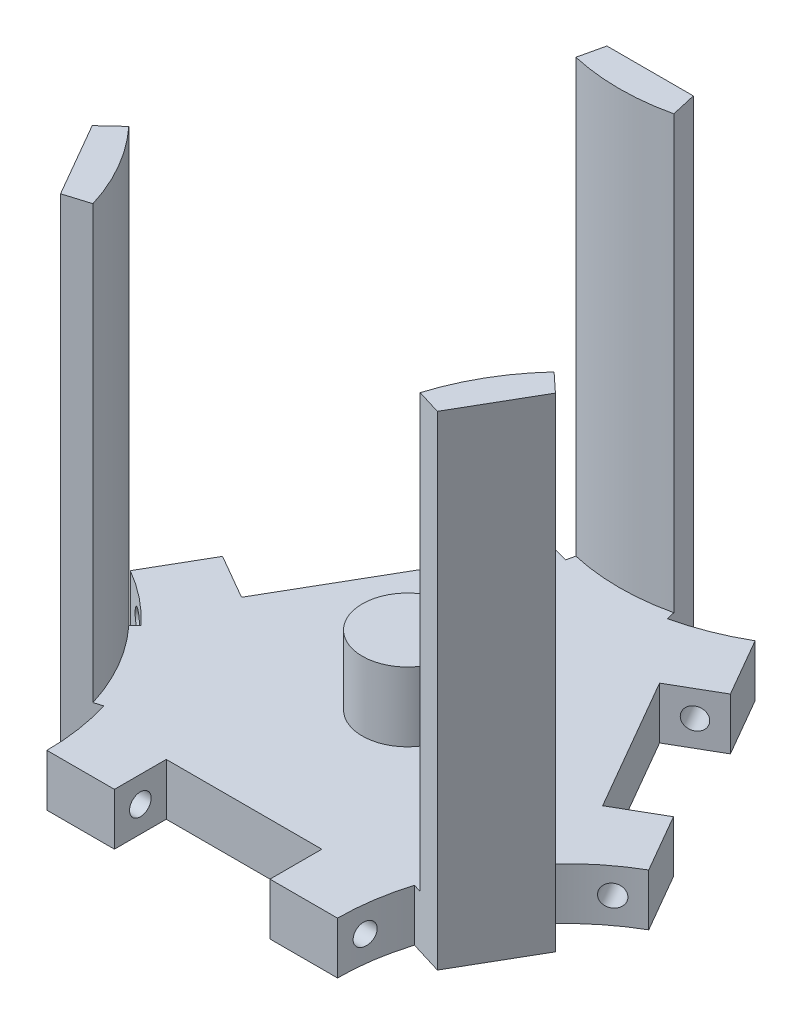
SolidWorks part; units mm, degrees
ref_plane "Front Plane" through (0, 0, 0) normal (0, 0, 1) x (1, 0, 0)
ref_plane "Top Plane" through (0, 0, 0) normal (0, 1, 0) x (1, 0, 0)
ref_plane "Right Plane" through (0, 0, 0) normal (1, 0, 0) x (0, 0, -1)
sketch "Sketch1" plane through (0, 0, 0) normal (0, 1, 0) x (1, 0, 0)
  line L0 (0, 0) -> (43.1834, 0) construction
  line L1 (43.1834, 0) -> (21.5917, 37.3979) construction
  line L2 (21.5917, 37.3979) -> (0, 0) construction
  line L3 (6.5917, 11.4171) -> (15, 25.9808)
  line L4 (28.1834, 25.9808) -> (36.5917, 11.4171)
  line L5 (13.1834, 0) -> (30, 0)
  line L6 (10.7958, 18.6989) -> (21.5917, 12.466) construction
  line L7 (21.5917, 12.466) -> (32.3875, 18.6989) construction
  line L8 (21.5917, 12.466) -> (21.5917, 0) construction
  line L9 (0, 0) -> (21.5917, 12.466) construction
  line L10 (21.5917, 12.466) -> (43.1834, 0) construction
  line L11 (21.5917, 12.466) -> (21.5917, 37.3979) construction
  line L12 (9.6546, 8.9769) -> (8.1898, 7.6152)
  line L13 (12.6016, 3.8727) -> (10.6898, 3.285)
  line L14 (8.1898, 7.6152) -> (10.6898, 3.285)
  line L15 (33.5287, 8.9769) -> (34.9935, 7.6152)
  line L16 (30.5818, 3.8727) -> (32.4935, 3.285)
  line L17 (34.9935, 7.6152) -> (32.4935, 3.285)
  line L18 (18.6448, 24.5483) -> (19.0917, 26.4977)
  line L19 (24.5386, 24.5483) -> (24.0917, 26.4977)
  line L20 (19.0917, 26.4977) -> (24.0917, 26.4977)
  arc A3 (6.5917, 11.4171) -> (9.6546, 8.9769) centre (0.0017, 0.0029) cw
  arc A4 (13.1834, 0) -> (12.6016, 3.8727) centre (0.0034, 0) ccw
  arc A5 (36.5917, 11.4171) -> (33.5287, 8.9769) centre (43.1817, 0.0029) ccw
  arc A6 (30, 0) -> (30.5818, 3.8727) centre (43.18, 0) cw
  arc A7 (15, 25.9808) -> (18.6448, 24.5483) centre (21.59, 37.395) ccw
  arc A8 (28.1834, 25.9808) -> (24.5386, 24.5483) centre (21.5934, 37.395) cw
  point P9 (10.7958, 18.6989)
  point P10 (10.7958, 18.6989)
  point P11 (32.3875, 18.6989)
  point P12 (32.3875, 18.6989)
  point P13 (21.5917, 0)
  point P15 (21.5917, 0)
  point P18 (9.4398, 5.4501)
  point P33 (33.7435, 5.4501)
  point P39 (21.5917, 26.4977)
  dimension "D2" = 13.18
  dimension "D4" = 13.18
  dimension "D5" = 13.18
  dimension "D9" = 13.18
  dimension "D10" = 13.18
  dimension "D14" = 13.18
  dimension "D1" = 30
  dimension "D3" = 16.8166
  dimension "D6" = 2
  dimension "D7" = 2
  dimension "D8" = 5
  dimension "D11" = 2
  dimension "D12" = 2
  dimension "D13" = 5
  dimension "D15" = 2
  dimension "D16" = 2
  dimension "D17" = 60
  dimension "D18" = 5
extrude "Boss-Extrude1" add sketch "Sketch1" along normal blind 3 contours L4 A5 L15 L17 L16 A6 L5 A4 L13 L14 L12 A3 L3 A7 L18 L20 L19 A8
sketch "Sketch2" plane through (0, 3, 0) normal (0, 1, 0) x (1, 0, 0)
  line L0 (21.5917, 0) -> (21.5917, 12.466) construction
  line L1 (13.1834, 0) -> (30, 0) construction
  line L2 (10.7958, 18.6989) -> (21.5917, 12.466) construction
  line L3 (6.5917, 11.4171) -> (15, 25.9808) construction
  line L4 (21.5917, 12.466) -> (32.3875, 18.6989) construction
  line L5 (28.1834, 25.9808) -> (36.5917, 11.4171) construction
  circle A0 centre (21.5917, 12.466) radius 2.625
  dimension "D1" = 5.25
extrude "Boss-Extrude2" add sketch "Sketch2" along normal blind 4
sketch "Sketch3" plane through (0, 0, 0) normal (0, -1, 0) x (1, 0, 0)
  line L0 (17.0917, 0) -> (17.0917, -3)
  line L1 (13.1834, 0) -> (30, 0) construction
  line L2 (17.0917, -3) -> (26.0917, -3)
  line L3 (26.0917, -3) -> (26.0917, 0)
  line L4 (26.0917, 0) -> (17.0917, 0)
  line L5 (6.5917, -11.4171) -> (8.5458, -14.8018) construction
  line L6 (13.0458, -22.5961) -> (15, -25.9808) construction
  line L7 (8.5458, -14.8018) -> (13.0458, -22.5961)
  line L8 (6.5917, -11.4171) -> (15, -25.9808) construction
  line L9 (13.0458, -22.5961) -> (15.6439, -21.0961)
  line L10 (15.6439, -21.0961) -> (11.1439, -13.3018)
  line L11 (11.1439, -13.3018) -> (8.5458, -14.8018)
  line L12 (28.1834, -25.9808) -> (30.1375, -22.5961) construction
  line L13 (34.6375, -14.8018) -> (36.5917, -11.4171) construction
  line L14 (34.6375, -14.8018) -> (32.0394, -13.3018)
  line L15 (28.1834, -25.9808) -> (36.5917, -11.4171) construction
  line L16 (32.0394, -13.3018) -> (27.5394, -21.0961)
  line L17 (27.5394, -21.0961) -> (30.1375, -22.5961)
  line L18 (30.1375, -22.5961) -> (34.6375, -14.8018)
  line L19 (17.0917, 0) -> (13.1834, 0) construction
  line L20 (26.0917, 0) -> (30, 0) construction
  dimension "D1" = 9
  dimension "D2" = 3
  dimension "D3" = 9
  dimension "D4" = 3
  dimension "D5" = 9
  dimension "D6" = 3
extrude "Cut-Extrude1" cut sketch "Sketch3" against normal through all
sketch "Sketch4" plane through (2.25, 0, 3.8971) normal (-0.5, 0, -0.866) x (-0.866, 0, 0.5)
  line L0 (-34.3979, 3) -> (-37.3979, 3) construction
  line L1 (-37.3979, 3) -> (-37.3979, 0) construction
  circle A0 centre (-35.8979, 1.5) radius 0.625
  dimension "D1" = 1.25
  dimension "D2" = 1.5
  dimension "D3" = 1.5
extrude "Cut-Extrude2" cut sketch "Sketch4" against normal through all and the other way through all
sketch "Sketch5" plane through (8.5458, 0, -14.8018) normal (0.5, 0, -0.866) x (-0.866, 0, -0.5)
  line L0 (-3, 0) -> (0, 0) construction
  line L1 (0, 3) -> (0, 0) construction
  circle A0 centre (-1.5, 1.5) radius 0.625
  dimension "D1" = 1.25
  dimension "D2" = 1.5
  dimension "D3" = 1.5
extrude "Cut-Extrude3" cut sketch "Sketch5" against normal through all and the other way through all
sketch "Sketch6" plane through (26.0917, 0, 0) normal (-1, 0, 0) x (0, 0, 1)
  line L0 (0, 3) -> (-3, 3) construction
  line L1 (0, 3) -> (0, 0) construction
  circle A0 centre (-1.5, 1.5) radius 0.625
  dimension "D1" = 1.25
  dimension "D2" = 1.5
  dimension "D3" = 1.5
extrude "Cut-Extrude4" cut sketch "Sketch6" against normal through all and the other way through all
sketch "Sketch7" plane through (0, 3, 0) normal (0, 1, 0) x (1, 0, 0)
  line L1 (8.1898, 7.6152) -> (10.6898, 3.285)
  line L4 (32.4935, 3.285) -> (34.9935, 7.6152)
  line L7 (19.0917, 26.4977) -> (24.0917, 26.4977)
  line L9 (19.0917, 26.4977) -> (18.7565, 25.0356)
  line L10 (18.6448, 24.5483) -> (19.0917, 26.4977) construction
  line L11 (24.0917, 26.4977) -> (24.4269, 25.0356)
  line L12 (24.5386, 24.5483) -> (24.0917, 26.4977) construction
  line L13 (8.1898, 7.6152) -> (9.2884, 8.6365)
  line L14 (9.6546, 8.9769) -> (8.1898, 7.6152) construction
  line L15 (10.6898, 3.285) -> (12.1236, 3.7258)
  line L16 (12.6016, 3.8727) -> (10.6898, 3.285) construction
  line L17 (34.9935, 7.6152) -> (33.8949, 8.6365)
  line L18 (33.5287, 8.9769) -> (34.9935, 7.6152) construction
  line L19 (32.4935, 3.285) -> (31.0597, 3.7258)
  line L20 (30.5818, 3.8727) -> (32.4935, 3.285) construction
  arc A3 (18.7565, 25.0356) -> (24.4269, 25.0356) centre (21.5917, 37.4023) ccw
  arc A4 (33.8949, 8.6365) -> (31.0597, 3.7258) centre (43.1872, -0.0022) ccw
  arc A5 (9.2884, 8.6365) -> (12.1236, 3.7258) centre (-0.0038, -0.0022) cw
  dimension "D1" = 1.5
  dimension "D2" = 1.5
  dimension "D3" = 1.5
  dimension "D4" = 1.5
  dimension "D5" = 1.5
  dimension "D6" = 1.5
extrude "Boss-Extrude3" add sketch "Sketch7" along normal blind 25
scale "Scale1" scale about centroid uniform scaling yes scale factor 1.3
